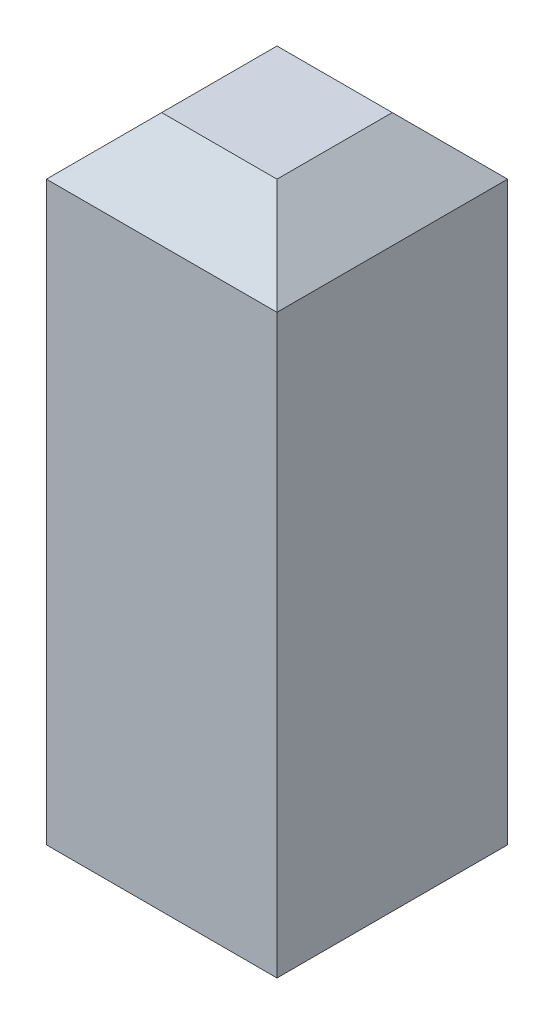
SolidWorks part; units mm, degrees
ref_plane "Front Plane" through (0, 0, 0) normal (0, 0, 1) x (1, 0, 0)
ref_plane "Top Plane" through (0, 0, 0) normal (0, 1, 0) x (1, 0, 0)
ref_plane "Right Plane" through (0, 0, 0) normal (1, 0, 0) x (0, 0, -1)
sketch "Sketch1" plane through (0, 0, 0) normal (0, 1, 0) x (1, 0, 0)
  line L1 (-2, -2) -> (2, -2)
  line L2 (-2, -2) -> (-2, 2)
  line L3 (-2, 2) -> (2, 2)
  line L4 (2, -2) -> (2, 2)
  line L5 (-2, -2) -> (2, 2) construction
  line L6 (-2, 2) -> (2, -2) construction
  point P0 (0, 0)
  dimension "D1" = 4
  dimension "D2" = 4
extrude "Boss-Extrude1" add sketch "Sketch1" along normal blind 12
chamfer "Chamfer3" distance 1 angle 45 4 edges at (0, 12, 2) (-2, 12, 0) (0, 12, -2) (2, 12, 0)
chamfer "Chamfer4" distance 1 angle 45 4 edges at (-2, 0, 0) (0, 0, -2) (2, 0, 0) (0, 0, 2)
